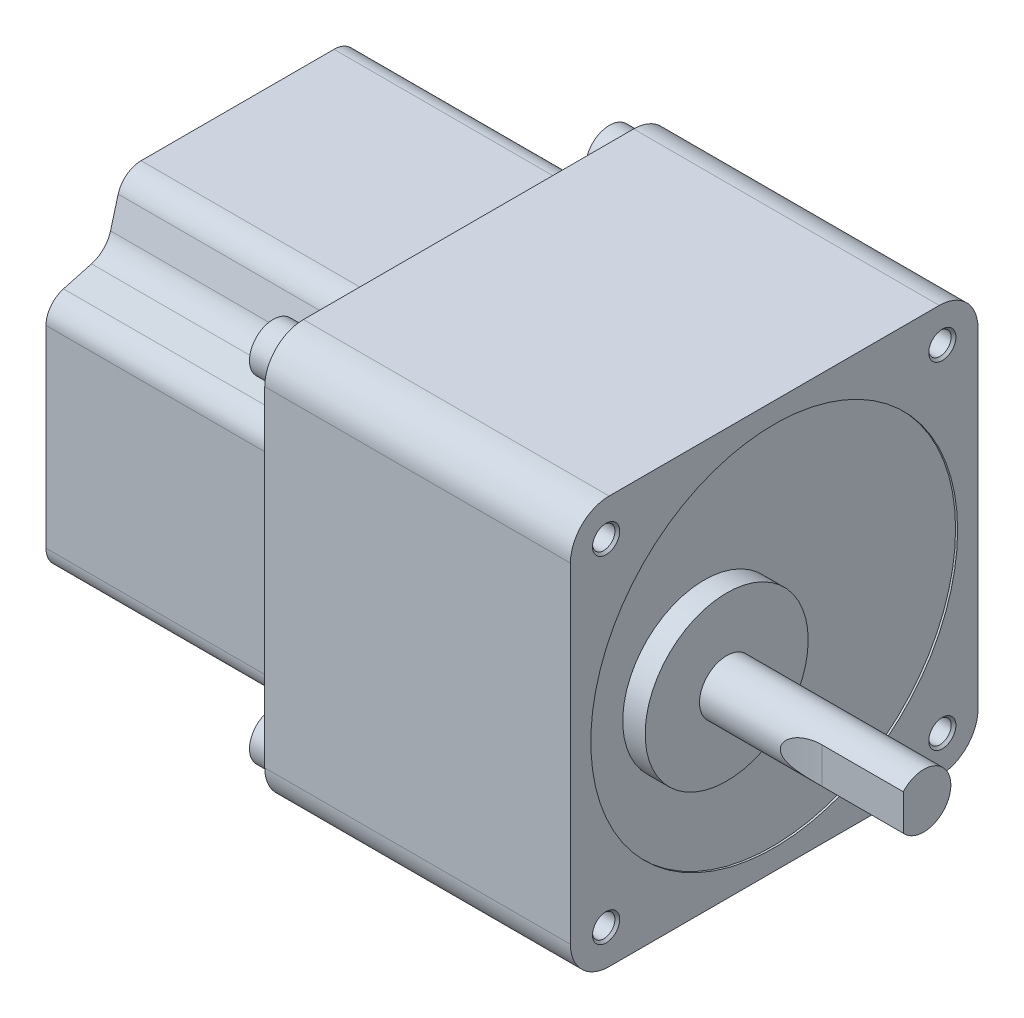
SolidWorks part; units mm, degrees
ref_plane "Front" through (0, 0, 0) normal (0, 0, 1) x (1, 0, 0)
ref_plane "Top" through (0, 0, 0) normal (0, 1, 0) x (1, 0, 0)
ref_plane "Right" through (0, 0, 0) normal (1, 0, 0) x (0, 0, -1)
sketch "Sketch1" plane through (0, 0, 0) normal (1, 0, 0) x (0, 0, -1)
  line L0 (75.0921, 0) -> (-14.1917, 0) construction
  line L1 (0, -30) -> (60, -30)
  line L2 (0, -30) -> (0, 30)
  line L3 (0, 30) -> (60, 30)
  line L4 (60, -30) -> (60, 30)
  dimension "D1" = 60
extrude "Boss-Extrude1" add sketch "Sketch1" against normal blind 45
sketch "Sketch2" plane through (-45, 0, 0) normal (-1, 0, 0) x (0, 0, 1)
  line L0 (-1.8, 16.87) -> (-1.8, -16.87)
  line L1 (-1.8, -16.87) -> (-10.6982, -19.3018)
  line L2 (-10.6982, -19.3018) -> (-13.13, -28.2)
  line L3 (-13.13, -28.2) -> (-46.87, -28.2)
  line L4 (-46.87, -28.2) -> (-49.3018, -19.3018)
  line L5 (-49.3018, -19.3018) -> (-58.2, -16.87)
  line L6 (-58.2, -16.87) -> (-58.2, 16.87)
  line L7 (-58.2, 16.87) -> (-49.3018, 19.3018)
  line L8 (-49.3018, 19.3018) -> (-46.87, 28.2)
  line L9 (-46.87, 28.2) -> (-13.13, 28.2)
  line L10 (-13.13, 28.2) -> (-10.6982, 19.3018)
  line L11 (-10.6982, 19.3018) -> (-1.8, 16.87)
  line L12 (0, 0) -> (-60, 0) construction
  line L13 (-60, -30) -> (-60, 30) construction
  line L14 (-30, 30) -> (-30, -30) construction
  line L17 (-60, 30) -> (0, 30) construction
  line L18 (0, -30) -> (-60, -30) construction
  dimension "D1" = 56.4
  dimension "D2" = 56.4
  dimension "D3" = 33.74
  dimension "D4" = 30.57
extrude "Boss-Extrude2" add sketch "Sketch2" along normal blind 34
sketch "Sketch3" plane through (-45, 0, 0) normal (-1, 0, 0) x (0, 0, 1)
  line L0 (0, 0) -> (-60, 0) construction
  line L1 (-30, 0) -> (-5.2513, 24.7487) construction
  line L2 (-60, -30) -> (-60, 30) construction
  line L5 (-30, 30) -> (-30, -30) construction
  line L6 (-60, 30) -> (0, 30) construction
  line L7 (0, -30) -> (-60, -30) construction
  circle A0 centre (-5.2513, 24.7487) radius 3.5
  circle A1 centre (-5.2513, -24.7487) radius 3.5
  circle A2 centre (-54.7487, -24.7487) radius 3.5
  circle A3 centre (-54.7487, 24.7487) radius 3.5
  circle A4 centre (-30, 0) radius 35 construction
  dimension "D1" = 7
  dimension "D2" = 70
  dimension "D3" = 45
extrude "Boss-Extrude3" add sketch "Sketch3" along normal blind 4
sketch "Sketch4" plane through (0, 0, -58.2) normal (0, 0, -1) x (-1, 0, 0)
  line L0 (0, -30) -> (0, 30) construction
  circle A0 centre (71, 0) radius 4.5
  dimension "D1" = 71
  dimension "D2" = 9
extrude "Boss-Extrude4" add sketch "Sketch4" along normal blind 1.5
sketch "Sketch5" plane through (0, 0, -59.7) normal (0, 0, -1) x (-1, 0, 0)
  line L0 (71, -4.5) -> (71, 4.5) construction
  line L1 (75.5, 0) -> (66.5, 0) construction
  circle A0 centre (73, -2) radius 0.5
  circle A1 centre (73, 0) radius 0.5
  circle A2 centre (73, 2) radius 0.5
  circle A3 centre (69, -2) radius 0.5
  circle A4 centre (69, 0) radius 0.5
  circle A5 centre (69, 2) radius 0.5
  circle A6 centre (71, 0) radius 4.5 construction
  circle A7 centre (71, 0) radius 4.5 construction
  dimension "D1" = 1
  dimension "D2" = 2
  dimension "D3" = 2
  dimension "D4" = 4
extrude "Boss-Extrude5" add sketch "Sketch5" along normal blind 8.5
sketch "Sketch6" plane through (0, 0, 0) normal (1, 0, 0) x (0, 0, -1)
  line L3 (30, -30) -> (30, 30) construction
  line L4 (0, -30) -> (60, -30) construction
  line L5 (60, 30) -> (0, 30) construction
  circle A0 centre (30, 0) radius 27
  dimension "D1" = 54
extrude "Cut-Extrude1" cut sketch "Sketch6" against normal blind 0.3
sketch "Sketch7" plane through (-0.3, 0, 0) normal (1, 0, 0) x (0, 0, -1)
  line L0 (0, 30) -> (0, -30) construction
  circle A0 centre (20, 0) radius 12
  dimension "D1" = 20
  dimension "D2" = 24
extrude "Boss-Extrude6" add sketch "Sketch7" along normal blind 3.3
sketch "Sketch8" plane through (3, 0, 0) normal (1, 0, 0) x (0, 0, -1)
  circle A0 centre (20, 0) radius 4
  dimension "D1" = 8
extrude "Boss-Extrude7" add sketch "Sketch8" along normal blind 29
sketch "Sketch9" plane through (0, 0, 0) normal (0, 1, 0) x (1, 0, 0)
  line L0 (32, 17) -> (20, 17)
  line L1 (32, 16) -> (32, 24) construction
  line L2 (32, 24) -> (3, 24) construction
  line L3 (32, 17) -> (32, 16)
  line L4 (32, 16) -> (14.8971, 16)
  line L5 (3, 16) -> (32, 16) construction
  arc A0 (20, 17) -> (14.8971, 16) centre (20, 3.48) ccw
  dimension "D3" = 13.52
  dimension "D1" = 12
  dimension "D2" = 7
extrude "Cut-Extrude2" cut sketch "Sketch9" against normal through all and the other way through all
hole_wizard "M4 Tapped Hole1" positions "Sketch11" profile "Sketch10" tap size "M4" standard "ISO"
sketch "Sketch11" plane through (0, 0, 0) normal (1, 0, 0) x (0, 0, -1)
  line L4 (-7.096, 0) -> (72.8982, 0) construction
  line L6 (30, -30) -> (30, 42.1922) construction
  line L8 (0, -30) -> (60, -30) construction
  line L9 (5.2513, -24.7487) -> (30, 0) construction
  circle A2 centre (30, 0) radius 35
  point P0 (5.2513, -24.7487)
  point P1 (5.2513, 24.7487)
  point P3 (54.7487, -24.7487)
  point P5 (54.7487, 24.7487)
  dimension "D1" = 70
  dimension "D2" = 45
sketch "Sketch10" plane through (0, -24.7487, -5.2513) normal (0, 1, 0) x (0, 0, -1)
  line L0 (0, 0) -> (0, 11.0914)
  line L1 (0, 11.0914) -> (1.65, 10.1)
  line L2 (1.65, 10.1) -> (1.65, 0.35)
  line L3 (1.65, 0.35) -> (2, 0)
  line L5 (2, 0) -> (0, 0)
  line L6 (-1.65, 0.35) -> (-2, 0) construction
  line L10 (0, 11.0914) -> (-1.65, 10.1) construction
  line L11 (0, -6.35) -> (0, 107.95) construction
  dimension "Tap Drill Dia." = 3.3
  dimension "Tap Drill Depth" = 10.1
  dimension "Near C'Sink Dia." = 4
  dimension "Near C'Sink Angle" = 90
  dimension "Drill Angle" = 118
cosmetic thread "Hole Thread1" parameters "D1"=8, "D2"=4
cosmetic thread "Hole Thread2" parameters "D1"=8, "D2"=4
cosmetic thread "Hole Thread3" parameters "D1"=8, "D2"=4
cosmetic thread "Hole Thread4" parameters "D1"=8, "D2"=4
fillet "Fillet1" radius 3.5 8 edges at (-62, 28.2, -13.13) (-62, 28.2, -46.87) (-62, 16.87, -58.2) (-62, -16.87, -58.2) (-62, -28.2, -46.87) (-62, -28.2, -13.13) (-62, 16.87, -1.8) (-62, -16.87, -1.8)
fillet "Fillet2" radius 4 4 edges at (-62, 19.3018, -10.6982) (-62, 19.3018, -49.3018) (-62, -19.3018, -49.3018) (-62, -19.3018, -10.6982)
fillet "Fillet3" radius 5.7 4 edges at (-22.5, 30, -60) (-22.5, 30, 0) (-22.5, -30, -60) (-22.5, -30, 0)
